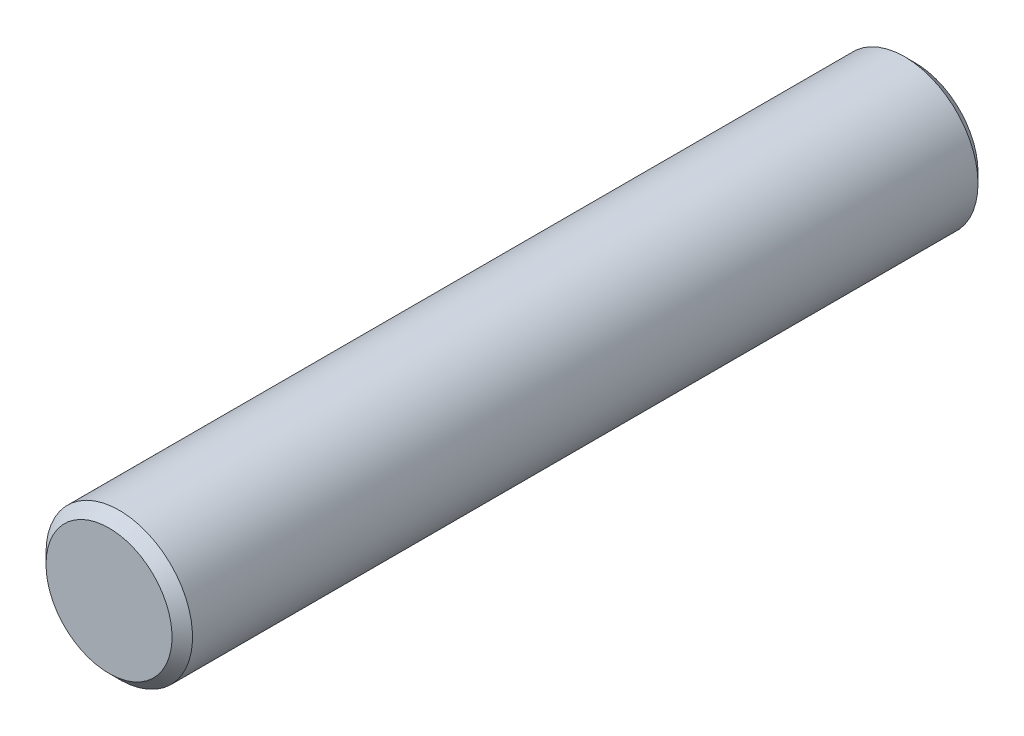
SolidWorks part; units mm, degrees
ref_plane "Přední rovina" through (0, 0, 0) normal (0, 0, 1) x (1, 0, 0)
ref_plane "Vrchní rovina" through (0, 0, 0) normal (0, 1, 0) x (1, 0, 0)
ref_plane "Pravá rovina" through (0, 0, 0) normal (1, 0, 0) x (0, 0, -1)
sketch "Skica1" plane through (0, 0, 0) normal (0, 0, 1) x (1, 0, 0)
  circle A0 centre (0, 0) radius 5
  dimension "M" = 10
extrude "Vysunout1" add sketch "Skica1" along normal blind 55
cosmetic thread "Kosmetický závit1" parameters "b"=26, "D2"=8.5
cosmetic thread "Kosmetický závit3" parameters "e"=10, "D2"=8.5
chamfer "Zkosit1" distance 0.7 angle 45 2 edges at (5, 0, 0) (5, 0, 55)
equation "\"D1@Zkosit1\" = \"M@Skica1\" * 0.07"
equation "\"D2@Kosmetický závit3\" = 0.85*\"M@Skica1\""
equation "\"D2@Kosmetický závit1\" = 0.85*\"M@Skica1\""
